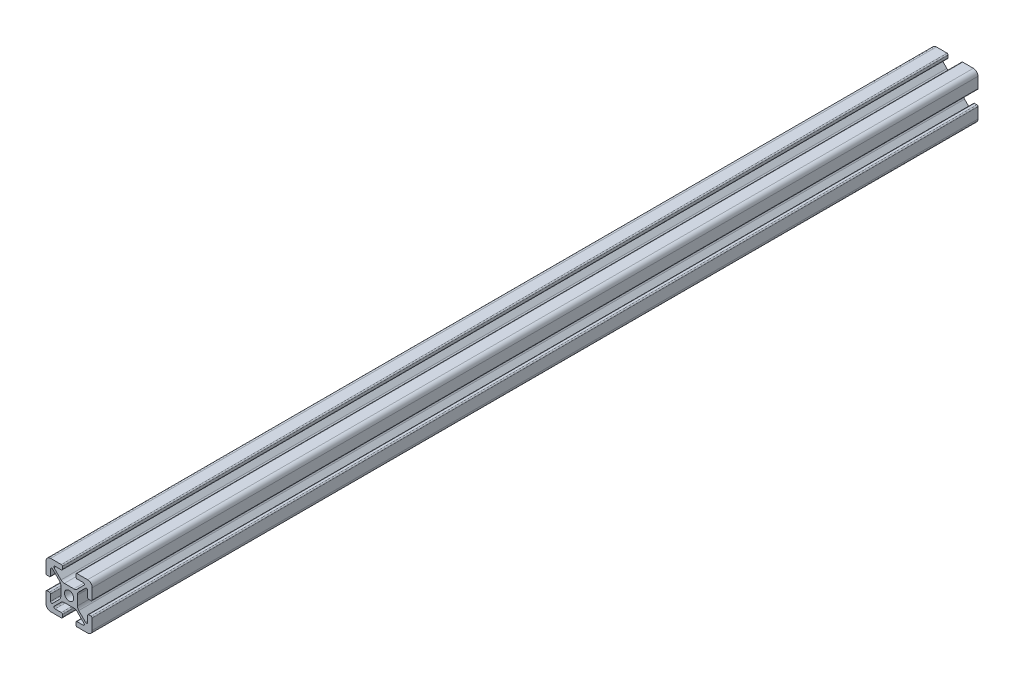
SolidWorks part; units mm, degrees
ref_plane "Front Plane" through (0, 0, 0) normal (0, 0, 1) x (1, 0, 0)
ref_plane "Top Plane" through (0, 0, 0) normal (0, 1, 0) x (1, 0, 0)
ref_plane "Right Plane" through (0, 0, 0) normal (1, 0, 0) x (0, 0, -1)
sketch "Sketch1" plane through (0, 0, 0) normal (0, 0, 1) x (1, 0, 0)
  line L0 (4.4179, 5.3159) -> (8.178, 9.076)
  line L1 (-10.16, -12.7) -> (-4.309, -12.7)
  line L2 (-12.7, -10.16) -> (-12.7, -4.309)
  line L3 (-10.16, 12.7) -> (-4.309, 12.7)
  line L4 (12.7, -10.16) -> (12.7, -4.309)
  line L5 (-12.7, -12.7) -> (12.7, 12.7) construction
  line L6 (-12.7, 12.7) -> (12.7, -12.7) construction
  line L7 (-2.6219, -4.572) -> (2.6219, -4.572)
  line L8 (-4.572, -2.6219) -> (-4.572, 2.6219)
  line L9 (-2.6219, 4.572) -> (2.6219, 4.572)
  line L10 (4.572, -2.6219) -> (4.572, 2.6219)
  line L11 (-4.572, -4.572) -> (4.572, 4.572) construction
  line L12 (-4.572, 4.572) -> (4.572, -4.572) construction
  line L13 (5.3159, 4.4179) -> (9.076, 8.178)
  line L14 (5.3159, -4.4179) -> (9.076, -8.178)
  line L15 (4.4179, -5.3159) -> (8.178, -9.076)
  line L16 (-4.4179, -5.3159) -> (-8.178, -9.076)
  line L17 (-5.3159, -4.4179) -> (-9.076, -8.178)
  line L18 (-5.3159, 4.4179) -> (-9.076, 8.178)
  line L19 (-4.4179, 5.3159) -> (-8.178, 9.076)
  line L20 (-3.674, 4.572) -> (-3.8683, 4.7663) construction
  line L21 (-10.16, 10.16) -> (10.16, 10.16) construction
  line L22 (-7.7289, 10.16) -> (-4.309, 10.16)
  line L23 (10.16, -7.7289) -> (10.16, -4.309)
  line L24 (-7.7289, -10.16) -> (-4.309, -10.16)
  line L25 (-10.16, -7.7289) -> (-10.16, -4.309)
  line L26 (-10.16, -10.16) -> (-10.16, 10.16) construction
  line L27 (-10.16, -10.16) -> (10.16, -10.16) construction
  line L28 (10.16, -10.16) -> (10.16, 10.16) construction
  line L29 (-4.572, 3.674) -> (-17.3082, 3.674) construction
  line L30 (-4.572, -3.674) -> (-17.7261, -3.674) construction
  line L31 (-17.7261, -3.674) -> (20.6347, -3.674) construction
  line L32 (-4.572, 3.674) -> (19.3811, 3.674) construction
  line L33 (-12.7, 4.309) -> (-12.7, 10.16)
  line L34 (-10.16, 4.309) -> (-10.16, 7.7289)
  line L35 (-12.7, -12.7) -> (-12.7, 12.7) construction
  line L36 (12.7, 4.309) -> (12.7, 10.16)
  line L37 (10.16, 4.309) -> (10.16, 7.7289)
  line L38 (12.7, -12.7) -> (12.7, 12.7) construction
  line L39 (-3.674, 10.795) -> (-3.674, 12.065)
  line L40 (3.674, 10.795) -> (3.674, 12.065)
  line L41 (-3.674, -10.795) -> (-3.674, -12.065)
  line L42 (3.674, -10.795) -> (3.674, -12.065)
  line L43 (4.309, -10.16) -> (7.7289, -10.16)
  line L44 (4.309, -12.7) -> (10.16, -12.7)
  line L45 (4.309, 12.7) -> (10.16, 12.7)
  line L46 (-12.7, -12.7) -> (12.7, -12.7) construction
  line L47 (4.309, 10.16) -> (7.7289, 10.16)
  line L48 (-12.7, 12.7) -> (12.7, 12.7) construction
  line L49 (-12.065, 3.674) -> (-10.795, 3.674)
  line L50 (-12.065, -3.674) -> (-10.795, -3.674)
  line L51 (10.795, -3.674) -> (12.065, -3.674)
  line L52 (12.065, 3.674) -> (10.795, 3.674)
  circle A0 centre (0, 0) radius 2.54
  arc A1 (5.3159, -4.4179) -> (4.572, -2.6219) centre (7.112, -2.6219) cw
  arc A2 (5.3159, 4.4179) -> (4.572, 2.6219) centre (7.112, 2.6219) ccw
  arc A3 (4.4179, 5.3159) -> (2.6219, 4.572) centre (2.6219, 7.112) cw
  arc A4 (-4.4179, 5.3159) -> (-2.6219, 4.572) centre (-2.6219, 7.112) ccw
  arc A5 (-5.3159, 4.4179) -> (-4.572, 2.6219) centre (-7.112, 2.6219) cw
  arc A6 (-5.3159, -4.4179) -> (-4.572, -2.6219) centre (-7.112, -2.6219) ccw
  arc A7 (4.4179, -5.3159) -> (2.6219, -4.572) centre (2.6219, -7.112) ccw
  arc A8 (-4.4179, -5.3159) -> (-2.6219, -4.572) centre (-2.6219, -7.112) cw
  arc A9 (-10.16, -12.7) -> (-12.7, -10.16) centre (-10.16, -10.16) cw
  arc A10 (10.16, -12.7) -> (12.7, -10.16) centre (10.16, -10.16) ccw
  arc A11 (10.16, 12.7) -> (12.7, 10.16) centre (10.16, 10.16) cw
  arc A12 (-12.7, 10.16) -> (-10.16, 12.7) centre (-10.16, 10.16) cw
  arc A13 (-7.7289, -10.16) -> (-8.178, -9.076) centre (-7.7289, -9.525) cw
  arc A14 (-10.16, -7.7289) -> (-9.076, -8.178) centre (-9.525, -7.7289) ccw
  arc A15 (10.16, -7.7289) -> (9.076, -8.178) centre (9.525, -7.7289) cw
  arc A16 (8.178, -9.076) -> (7.7289, -10.16) centre (7.7289, -9.525) cw
  arc A17 (9.076, 8.178) -> (10.16, 7.7289) centre (9.525, 7.7289) cw
  arc A18 (8.178, 9.076) -> (7.7289, 10.16) centre (7.7289, 9.525) ccw
  arc A19 (-7.7289, 10.16) -> (-8.178, 9.076) centre (-7.7289, 9.525) ccw
  arc A20 (-9.076, 8.178) -> (-10.16, 7.7289) centre (-9.525, 7.7289) ccw
  arc A21 (-10.16, -4.309) -> (-10.795, -3.674) centre (-10.795, -4.309) ccw
  arc A22 (-12.7, -4.309) -> (-12.065, -3.674) centre (-12.065, -4.309) cw
  arc A23 (-3.674, -12.065) -> (-4.309, -12.7) centre (-4.309, -12.065) cw
  arc A24 (-3.674, -10.795) -> (-4.309, -10.16) centre (-4.309, -10.795) ccw
  arc A25 (3.674, -10.795) -> (4.309, -10.16) centre (4.309, -10.795) cw
  arc A26 (3.674, -12.065) -> (4.309, -12.7) centre (4.309, -12.065) ccw
  arc A27 (10.16, -4.309) -> (10.795, -3.674) centre (10.795, -4.309) cw
  arc A28 (12.7, -4.309) -> (12.065, -3.674) centre (12.065, -4.309) ccw
  arc A29 (10.16, 4.309) -> (10.795, 3.674) centre (10.795, 4.309) ccw
  arc A30 (12.7, 4.309) -> (12.065, 3.674) centre (12.065, 4.309) cw
  arc A31 (4.309, 10.16) -> (3.674, 10.795) centre (4.309, 10.795) cw
  arc A32 (3.674, 12.065) -> (4.309, 12.7) centre (4.309, 12.065) cw
  arc A33 (-4.309, 10.16) -> (-3.674, 10.795) centre (-4.309, 10.795) ccw
  arc A34 (-3.674, 12.065) -> (-4.309, 12.7) centre (-4.309, 12.065) ccw
  arc A35 (-12.7, 4.309) -> (-12.065, 3.674) centre (-12.065, 4.309) ccw
  arc A36 (-10.16, 4.309) -> (-10.795, 3.674) centre (-10.795, 4.309) cw
  point P0 (0, 0)
  point P16 (1.8779, 6.3681)
  point P17 (12.7565, 17.2467)
  point P18 (2.7759, 5.47)
  point P20 (4.572, -3.674)
  point P28 (4.572, 3.674)
  point P31 (0, 0)
  point P32 (13.6546, 16.3486)
  point P66 (3.674, 4.572)
  point P110 (-10.16, -3.674)
  point P113 (-12.7, -3.674)
  point P120 (3.674, -10.16)
  point P123 (3.674, -12.7)
  point P126 (10.16, -3.674)
  point P129 (12.7, -3.674)
  point P132 (10.16, 3.674)
  point P135 (12.7, 3.674)
  point P140 (3.674, 12.7)
  point P147 (-12.7, 3.674)
  point P150 (-10.16, 3.674)
  dimension "D3" = 5.08
  dimension "D8" = 2.54
  dimension "D9" = 0.635
  dimension "D10" = 0.635
  dimension "D1" = 25.4
  dimension "D2" = 25.4
  dimension "D4" = 9.144
  dimension "D5" = 1.27
  dimension "D7" = 2.54
  dimension "D6" = 4
extrude "Boss-Extrude1" add sketch "Sketch1" along normal blind 486.918
